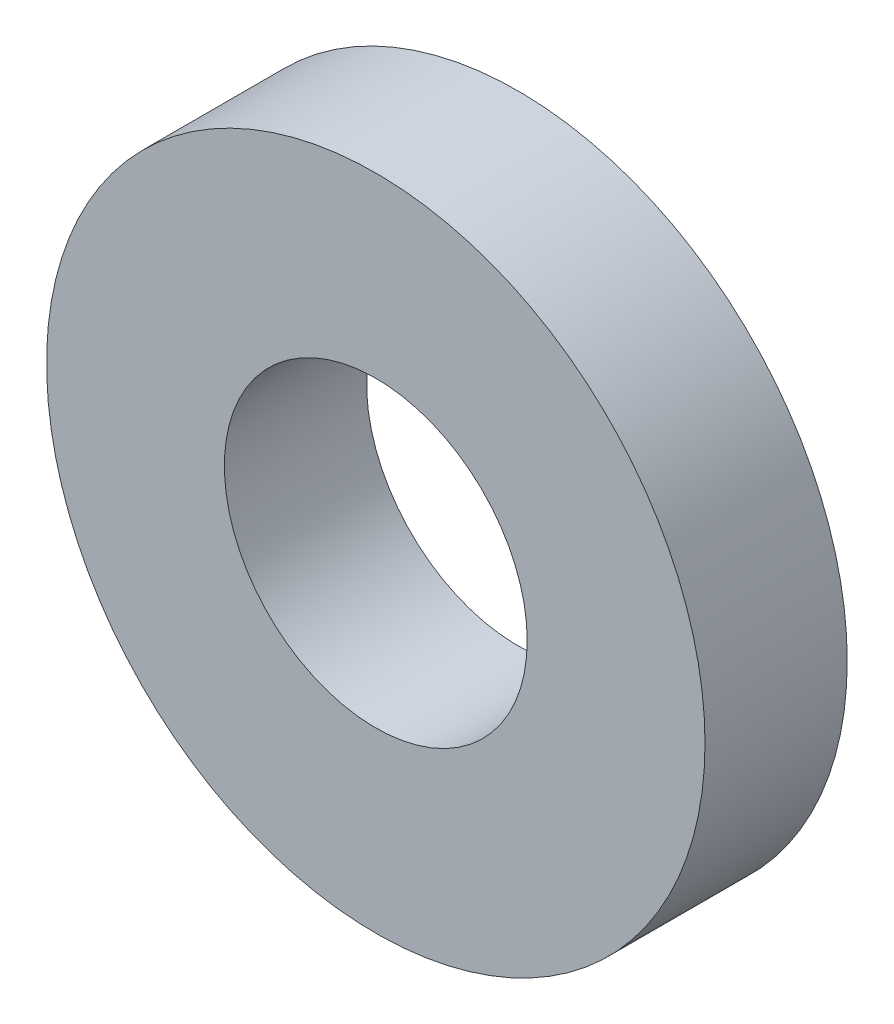
SolidWorks part; units mm, degrees
ref_plane "Front Plane" through (0, 0, 0) normal (0, 0, 1) x (1, 0, 0)
ref_plane "Top Plane" through (0, 0, 0) normal (0, 1, 0) x (1, 0, 0)
ref_plane "Right Plane" through (0, 0, 0) normal (1, 0, 0) x (0, 0, -1)
sketch "Sketch1" plane through (0, 0, 0) normal (0, 0, 1) x (1, 0, 0)
  circle A0 centre (0, 0) radius 2.921
  circle A1 centre (0, 0) radius 6.35
  dimension "ID" = 5.842
  dimension "OD" = 12.7
extrude "Extrude1" add sketch "Sketch1" against normal blind 2.7432
